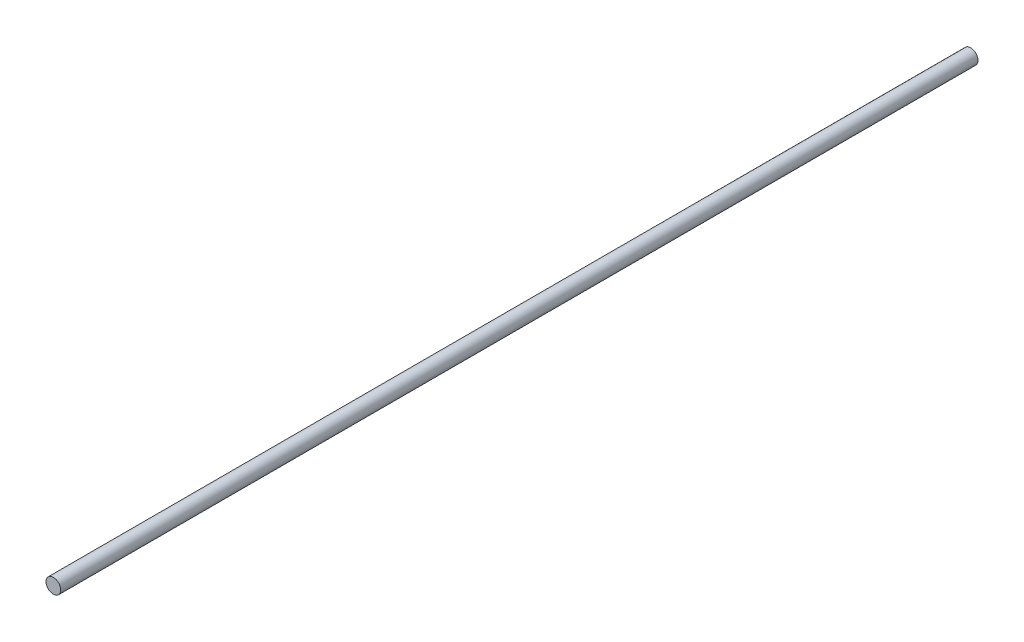
SolidWorks part; units mm, degrees
ref_plane "Front Plane" through (0, 0, 0) normal (0, 0, 1) x (1, 0, 0)
ref_plane "Top Plane" through (0, 0, 0) normal (0, 1, 0) x (1, 0, 0)
ref_plane "Right Plane" through (0, 0, 0) normal (1, 0, 0) x (0, 0, -1)
sketch "Sketch1" plane through (0, 0, 0) normal (0, 0, 1) x (1, 0, 0)
  circle A0 centre (0, 0) radius 8
extrude "Boss-Extrude1" add sketch "Sketch1" against normal blind 1000
